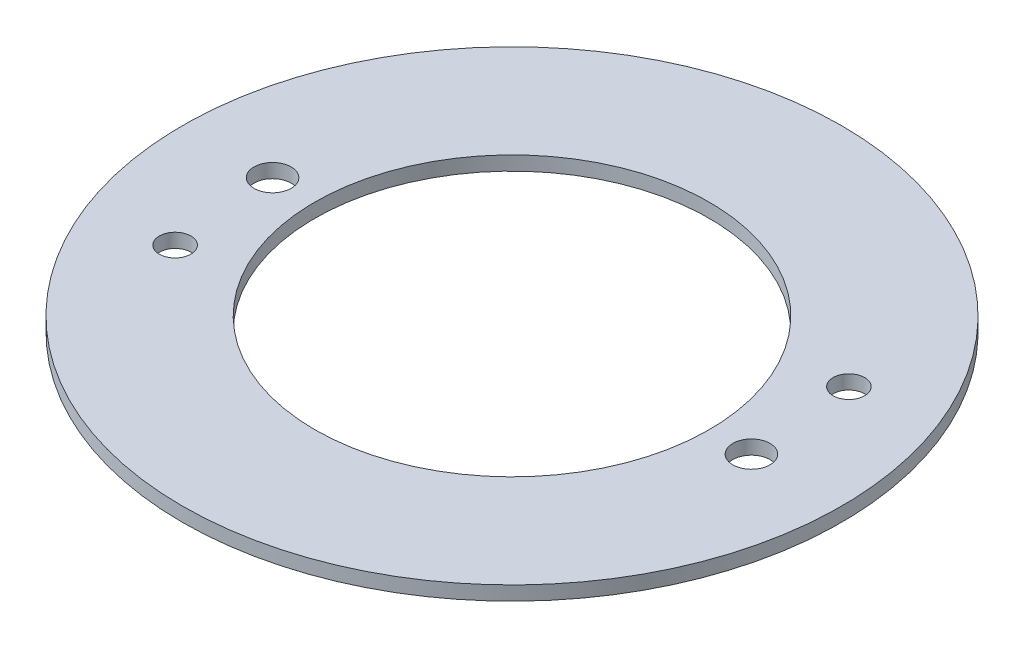
SolidWorks part; units mm, degrees
ref_plane "Front Plane" through (0, 0, 0) normal (0, 0, 1) x (1, 0, 0)
ref_plane "Top Plane" through (0, 0, 0) normal (0, 1, 0) x (1, 0, 0)
ref_plane "Right Plane" through (0, 0, 0) normal (1, 0, 0) x (0, 0, -1)
sketch "Sketch1" plane through (0, 0, 0) normal (0, 1, 0) x (1, 0, 0)
  circle A0 centre (0, 0) radius 74.295
extrude "Boss-Extrude1" add sketch "Sketch1" along normal blind 3.175
sketch "Sketch2" plane through (0, 3.175, 0) normal (0, 1, 0) x (1, 0, 0)
  line L0 (53.975, 0) -> (-53.975, 0) construction
  line L1 (51.7955, 24.1526) -> (-51.7955, -24.1526) construction
  circle A2 centre (-51.7955, -24.1526) radius 3.556
  circle A3 centre (51.7955, 24.1526) radius 3.556
  circle A4 centre (-53.975, 0) radius 4.191
  circle A5 centre (53.975, 0) radius 4.191
  point P3 (0, 0)
  point P4 (0, 0)
  point P9 (0, 0)
extrude "Cut-Extrude1" cut sketch "Sketch2" against normal blind 3.175
sketch "Sketch3" plane through (0, 3.175, 0) normal (0, 1, 0) x (1, 0, 0)
  circle A0 centre (0, 0) radius 44.45
extrude "Cut-Extrude2" cut sketch "Sketch3" against normal blind 3.175
